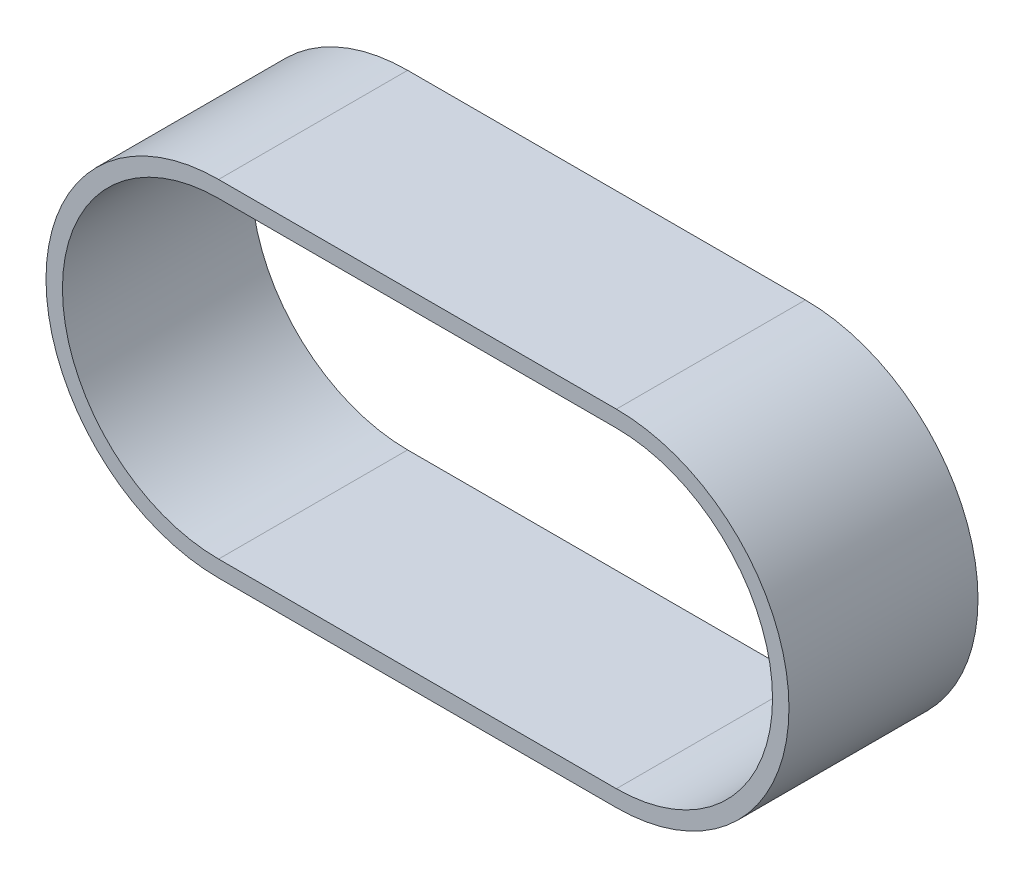
SolidWorks part; units mm, degrees
material "A2432/ Gomma"
ref_plane "Piano frontale" through (0, 0, 0) normal (0, 0, 1) x (1, 0, 0)
ref_plane "Piano superiore" through (0, 0, 0) normal (0, 1, 0) x (1, 0, 0)
ref_plane "Piano destro" through (0, 0, 0) normal (1, 0, 0) x (0, 0, -1)
sketch "Schizzo1" plane through (0, 0, 0) normal (0, 0, 1) x (1, 0, 0)
  line L0 (-121, 0) -> (121, 0) construction
  line L1 (-121, 95) -> (121, 95)
  line L2 (-121, -95) -> (121, -95)
  line L3 (-121, 0) -> (121, 0) construction
  line L4 (-121, 105) -> (121, 105)
  line L5 (-121, -105) -> (121, -105)
  arc A0 (-121, 95) -> (-121, -95) centre (-121, 0) ccw
  arc A1 (121, -95) -> (121, 95) centre (121, 0) ccw
  arc A2 (-121, 105) -> (-121, -105) centre (-121, 0) ccw
  arc A3 (121, -105) -> (121, 105) centre (121, 0) ccw
  point P2 (0, 0)
  point P7 (0, 0)
  dimension "D1" = 242
  dimension "D2" = 190
  dimension "D3" = 10
extrude "Estrusione-Estrusione1" add sketch "Schizzo1" along normal blind 115
ref_plane "Piano1" through (0, 0, 67.5) normal (0, 0, 1) x (1, 0, 0)
ref_plane "Piano2" through (0, 0, 47.5) normal (0, 0, 1) x (1, 0, 0)
